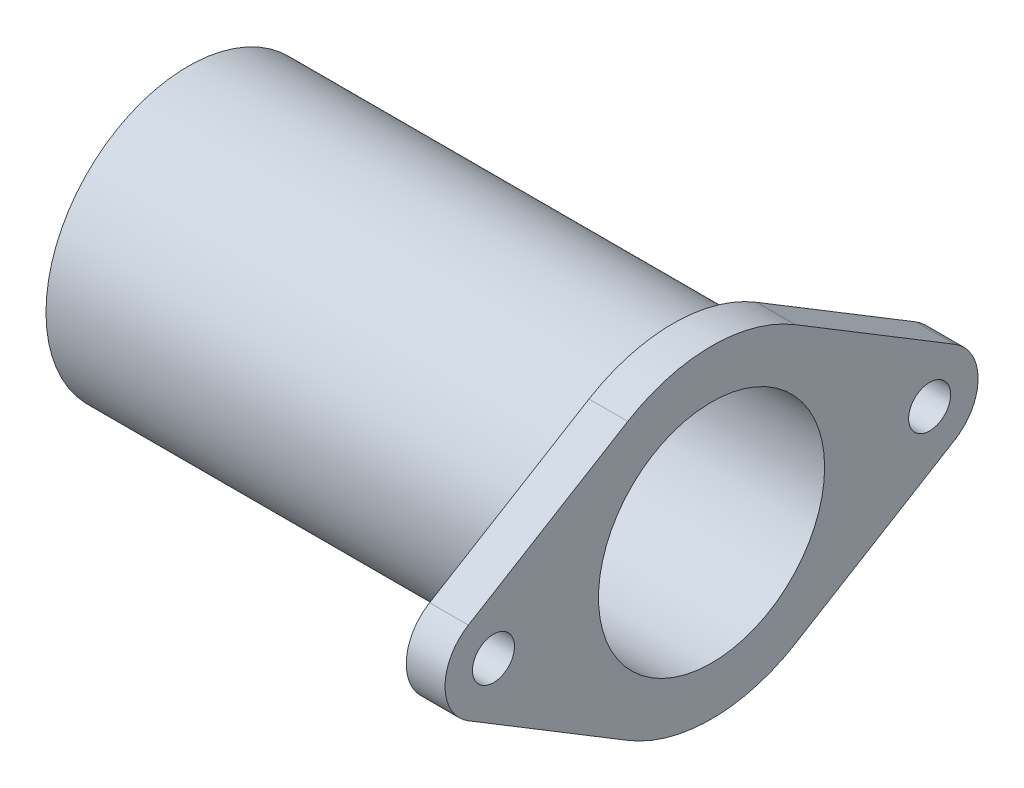
SolidWorks part; units mm, degrees
material "ASTM A36 Steel"
ref_plane "Front Plane" through (0, 0, 0) normal (0, 0, 1) x (1, 0, 0)
ref_plane "Top Plane" through (0, 0, 0) normal (0, 1, 0) x (1, 0, 0)
ref_plane "Right Plane" through (0, 0, 0) normal (1, 0, 0) x (0, 0, -1)
sketch "Sketch1" plane through (0, 0, 0) normal (1, 0, 0) x (0, 0, -1)
  circle A0 centre (0, 0) radius 44
  dimension "D1" = 88
extrude "Boss-Extrude1" add sketch "Sketch1" along normal blind 150
sketch "Sketch2" plane through (150, 0, 0) normal (1, 0, 0) x (0, 0, -1)
  line L0 (-25.9259, 42.7533) -> (-75.2778, 12.826)
  line L1 (25.9259, 42.7533) -> (75.2778, 12.826)
  line L2 (-75.2778, -12.826) -> (-25.9259, -42.7533)
  line L3 (75.2778, -12.826) -> (25.9259, -42.7533)
  arc A0 (25.9259, 42.7533) -> (-25.9259, 42.7533) centre (0, 0) ccw
  arc A1 (-75.2778, 12.826) -> (-75.2778, -12.826) centre (-67.5, 0) ccw
  arc A2 (75.2778, -12.826) -> (75.2778, 12.826) centre (67.5, 0) ccw
  arc A3 (-25.9259, -42.7533) -> (25.9259, -42.7533) centre (0, 0) ccw
  dimension "D1" = 100
  dimension "D2" = 30
  dimension "D3" = 30
  dimension "D4" = 67.5
  dimension "D5" = 67.5
extrude "Boss-Extrude2" add sketch "Sketch2" along normal blind 12
sketch "Sketch5" plane through (162, 0, 0) normal (1, 0, 0) x (0, 0, -1)
  circle A0 centre (67.5, 0) radius 6.5
  circle A1 centre (-67.5, 0) radius 6.5
  dimension "D1" = 13
  dimension "D2" = 13
extrude "Cut-Extrude3" cut sketch "Sketch5" against normal blind 80
sketch "Sketch6" plane through (162, 0, 0) normal (1, 0, 0) x (0, 0, -1)
  circle A0 centre (0, 0) radius 35
  dimension "D1" = 70
extrude "Cut-Extrude4" cut sketch "Sketch6" against normal blind 147
sketch "Sketch7" plane through (0, 0, 0) normal (-1, 0, 0) x (0, 0, 1)
  circle A0 centre (0, 0) radius 25.5
  dimension "D1" = 51
extrude "Cut-Extrude5" cut sketch "Sketch7" against normal blind 67
